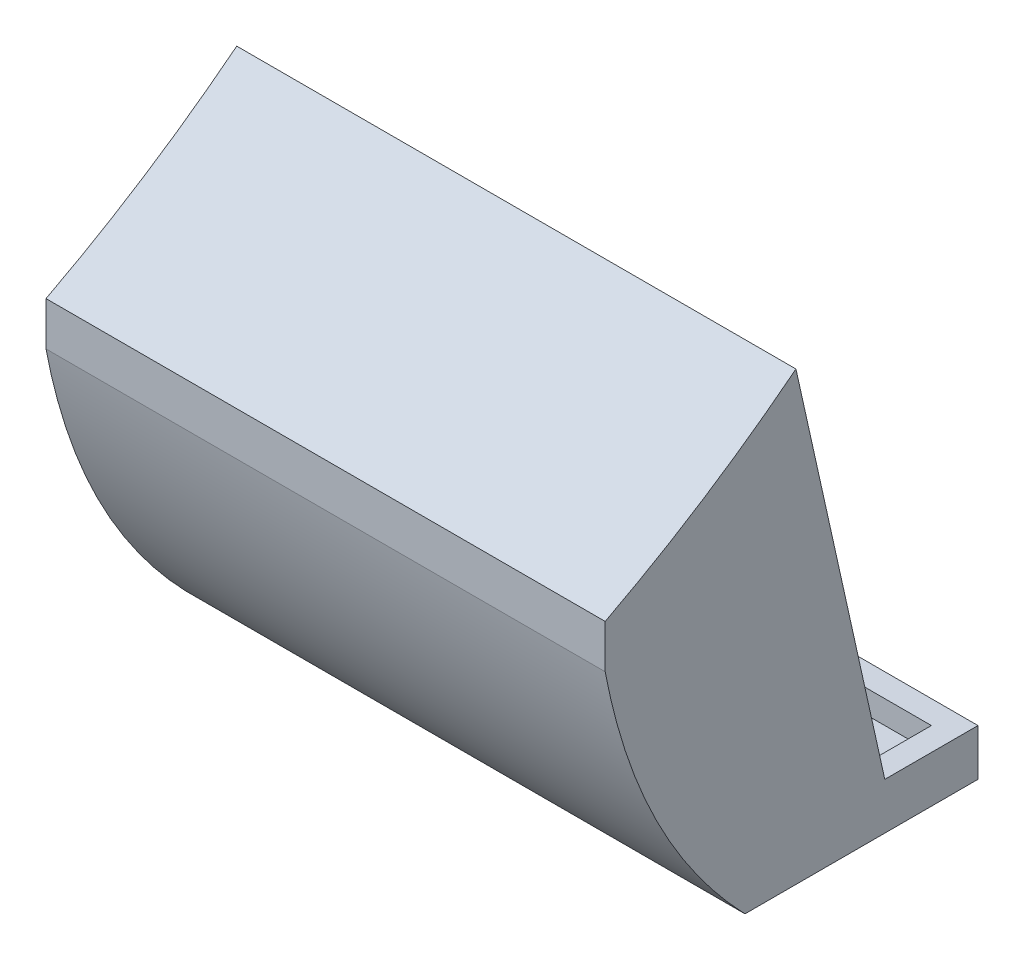
SolidWorks part; units mm, degrees
ref_plane "Front Plane" through (0, 0, 0) normal (0, 0, 1) x (1, 0, 0)
ref_plane "Top Plane" through (0, 0, 0) normal (0, 1, 0) x (1, 0, 0)
ref_plane "Right Plane" through (0, 0, 0) normal (1, 0, 0) x (0, 0, -1)
sketch "Sketch1" plane through (0, 0, 0) normal (0, 1, 0) x (1, 0, 0)
  line L1 (0, 0) -> (120, 0)
  line L2 (0, 0) -> (0, 80)
  line L3 (0, 80) -> (120, 80)
  line L4 (120, 0) -> (120, 80)
  dimension "D1" = 120
  dimension "D2" = 80
extrude "Boss-Extrude1" add sketch "Sketch1" along normal blind 100
sketch "Sketch2" plane through (120, 0, 0) normal (1, 0, 0) x (0, 0, -1)
  line L3 (80, 10) -> (60, 10)
  line L5 (40, 100) -> (60, 10)
  line L6 (0, 100) -> (80, 100) construction
  line L7 (80, 100) -> (80, 0) construction
  line L8 (40, 100) -> (80, 100)
  line L9 (80, 100) -> (80, 10)
  line L10 (0, 100) -> (0, 0) construction
  line L11 (0, 0) -> (80, 0) construction
  line L12 (0, 60) -> (0, 0)
  line L13 (0, 0) -> (30, 0)
  spline S0 degree 2 poles (0, 60) (6.7975, 24.0538) (30, 0) knots 0 0 0 0.927202 0.927202 0.927202
  dimension "D1" = 60
  dimension "D2" = 40
  dimension "D3" = 20
  dimension "D4" = 30
extrude "Cut-Extrude1" cut sketch "Sketch2" against normal through all
sketch "Sketch3" plane through (120, 0, 0) normal (1, 0, 0) x (0, 0, -1)
  line L0 (30, 0) -> (80, 0) construction
  circle A0 centre (-120, 300) radius 260
  dimension "D1" = 520
  dimension "D2" = 300
  dimension "D3" = 120
extrude "Cut-Extrude2" cut sketch "Sketch3" against normal through all
shell "Shell1" thickness 5
